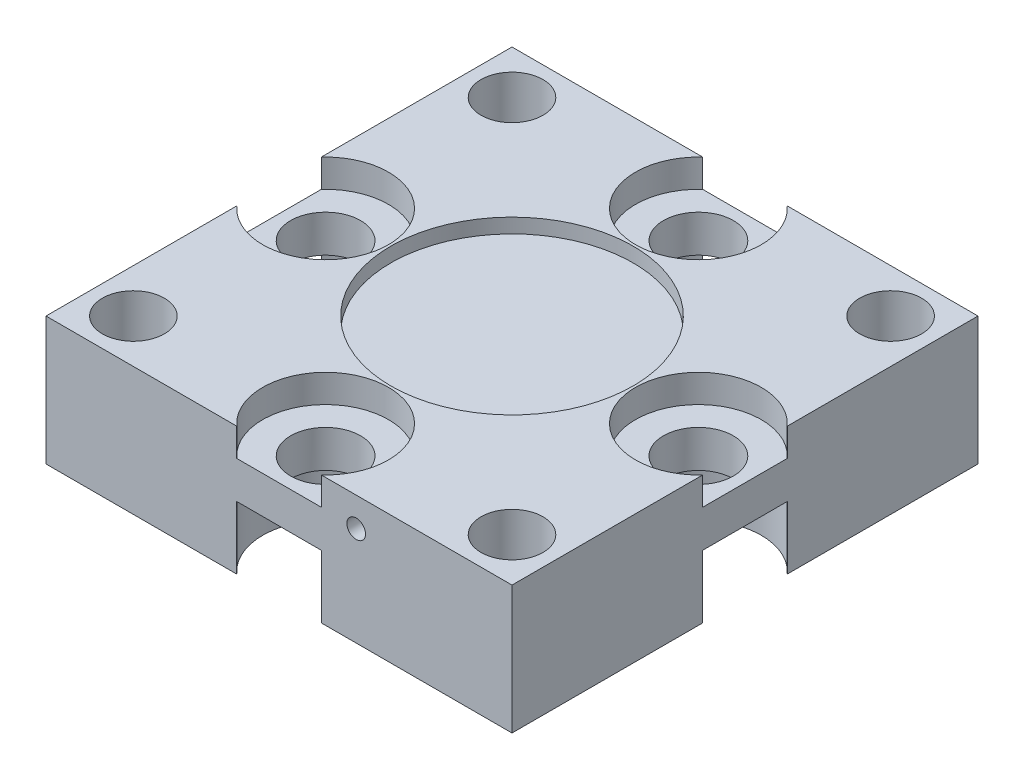
SolidWorks part; units mm, degrees
material "Copper"
ref_plane "Front Plane" through (0, 0, 0) normal (0, 0, 1) x (1, 0, 0)
ref_plane "Top Plane" through (0, 0, 0) normal (0, 1, 0) x (1, 0, 0)
ref_plane "Right Plane" through (0, 0, 0) normal (1, 0, 0) x (0, 0, -1)
sketch "Sketch1" plane through (0, 0, 0) normal (0, 1, 0) x (1, 0, 0)
  line L1 (-25.4, 25.4) -> (25.4, 25.4)
  line L2 (-25.4, 25.4) -> (-25.4, -25.4)
  line L3 (-25.4, -25.4) -> (25.4, -25.4)
  line L4 (25.4, 25.4) -> (25.4, -25.4)
  dimension "D1" = 50.8
  dimension "D2" = 50.8
  dimension "D3" = 25.4
  dimension "D4" = 25.4
extrude "Boss-Extrude1" add sketch "Sketch1" along normal blind 13.97
hole_wizard "1/4 Clearance Hole1" positions "Sketch4" profile "Sketch3" hole size "1/4" standard "ANSI Inch" end condition through all
sketch "Sketch4" plane through (0, 13.97, 0) normal (0, 1, 0) x (1, 0, 0)
  point P0 (-20.6375, -20.6375)
  point P2 (-20.6375, 20.6375)
  point P4 (20.6375, 20.6375)
  point P6 (20.6375, -20.6375)
sketch "Sketch3" plane through (-20.6375, 13.97, 20.6375) normal (1, 0, 0) x (0, 0, 1)
  line L0 (0, 0) -> (0, 13.97)
  line L1 (0, 13.97) -> (3.3782, 13.97)
  line L2 (3.3782, 13.97) -> (3.3782, 0)
  line L5 (3.3782, 0) -> (0, 0)
  line L11 (0, -6.35) -> (0, 107.95) construction
  dimension "Thru Hole Dia." = 6.7564
  dimension "Thru Hole Depth" = 13.97
sketch "Sketch5" plane through (0, 13.97, 0) normal (0, 1, 0) x (1, 0, 0)
  circle A0 centre (0, 0) radius 13.208
extrude "Cut-Extrude1" cut sketch "Sketch5" against normal blind 1.5875
sketch "Sketch6" plane through (0, 13.97, 0) normal (0, 1, 0) x (1, 0, 0)
  circle A0 centre (0, 20.32) radius 3.81
  circle A1 centre (20.32, 0) radius 3.81
  circle A2 centre (0, -20.32) radius 3.81
  circle A3 centre (-20.32, 0) radius 3.81
  dimension "D1" = 7.62
  dimension "." = 20.32
  dimension "D3" = 20.32
  dimension "D4" = 20.32
  dimension "D5" = 20.32
extrude "Cut-Extrude2" cut sketch "Sketch6" against normal through all
sketch "Sketch10" plane through (0, 13.97, 0) normal (0, 1, 0) x (1, 0, 0)
  circle A0 centre (-20.32, 0) radius 6.858
  circle A1 centre (0, 20.32) radius 6.858
  circle A2 centre (20.32, 0) radius 6.858
  circle A3 centre (0, -20.32) radius 6.858
extrude "Cut-Extrude3" cut sketch "Sketch10" against normal blind 3.048
sketch "Sketch11" plane through (0, 0, 0) normal (0, -1, 0) x (1, 0, 0)
  circle A0 centre (-20.32, 0) radius 6.858
  circle A1 centre (0, 20.32) radius 6.858
  circle A2 centre (20.32, 0) radius 6.858
  circle A3 centre (0, -20.32) radius 6.858
extrude "Cut-Extrude4" cut sketch "Sketch11" against normal blind 6.858
sketch "Sketch12" plane through (0, 0, 25.4) normal (0, 0, 1) x (1, 0, 0)
  line L0 (4.6071, 13.97) -> (25.4, 13.97) construction
  line L1 (4.6071, 13.97) -> (4.6071, 10.922) construction
  circle A0 centre (8.4171, 10.795) radius 1.016
  point P4 (4.6071, 12.446)
  dimension "D1" = 3.175
  dimension "D2" = 3.81
extrude "Cut-Extrude5" cut sketch "Sketch12" against normal blind 19.05
sketch "Sketch13" plane through (0, 0, -25.4) normal (0, 0, -1) x (-1, 0, 0)
  circle A0 centre (-8.4171, 10.795) radius 1.016
extrude "Cut-Extrude6" cut sketch "Sketch13" against normal blind 19.05
